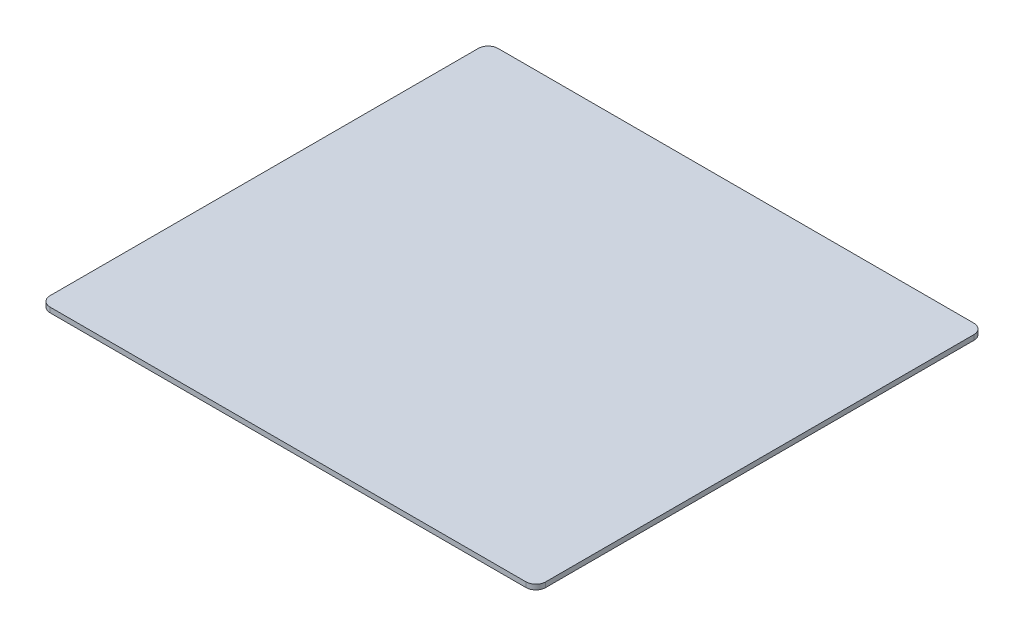
SolidWorks part; units mm, degrees
ref_plane "Front Plane" through (0, 0, 0) normal (0, 0, 1) x (1, 0, 0)
ref_plane "Top Plane" through (0, 0, 0) normal (0, 1, 0) x (1, 0, 0)
ref_plane "Right Plane" through (0, 0, 0) normal (1, 0, 0) x (0, 0, -1)
sketch "Sketch1" plane through (0, 0, 0) normal (0, 1, 0) x (1, 0, 0)
  line L0 (-130.625, 184.7613) -> (351.9808, 184.7613) construction
  line L1 (0, 0) -> (158.75, 0)
  line L2 (0, 0) -> (0, 143.4863)
  line L3 (193.2286, 178.4113) -> (329.3126, 178.4113) construction
  line L4 (158.75, 0) -> (158.75, 143.4863)
  line L19 (158.75, 143.4863) -> (0, 143.4863)
  line L21 (351.9786, 184.7613) -> (351.9786, -3.4747) construction
  point P1 (193.2286, 144.7467)
  point P2 (329.3126, 178.8928)
  point P4 (0, 0)
  point P5 (0.9294, 0.5153)
  point P7 (0, 0)
  dimension "D1" = 6.35
  dimension "D2" = 351.9786
  dimension "D5" = 158.75
  dimension "D6" = 34.925
extrude "Boss-Extrude1" add sketch "Sketch1" along normal blind 1.6002
fillet "Fillet1" radius 3.175 4 edges at (158.75, 0.8001, 0) (0, 0.8001, -143.4863) (158.75, 0.8001, -143.4863) (0, 0.8001, 0)
